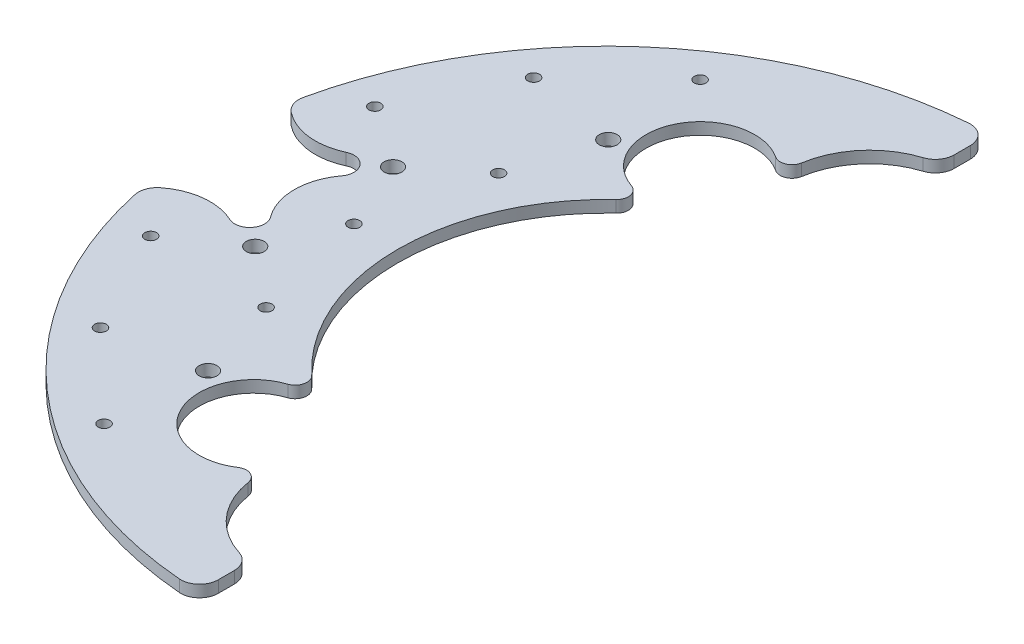
SolidWorks part; units mm, degrees
material "G-10 Garolite"
ref_plane "Front Plane" through (0, 0, 0) normal (0, 0, 1) x (1, 0, 0)
ref_plane "Top Plane" through (0, 0, 0) normal (0, 1, 0) x (1, 0, 0)
ref_plane "Right Plane" through (0, 0, 0) normal (1, 0, 0) x (0, 0, -1)
sketch "Sketch1" plane through (0, 0, 0) normal (0, 1, 0) x (1, 0, 0)
  line L0 (0, 0) -> (0, 53.6196) construction
  line L1 (0, 0) -> (0, -53.6196) construction
  line L2 (-1.5875, 53.5961) -> (-1.5875, 46.7173)
  line L3 (-1.5875, -46.7173) -> (-1.5875, -53.5961)
  arc A0 (-7.2005, 27.2547) -> (-7.2005, -27.2547) centre (0, 0) ccw
  arc A1 (-1.5875, 53.5961) -> (-52.743, 9.6559) centre (0, 0) ccw
  circle A4 centre (-28.468, 38.9692) radius 0.7937
  circle A6 centre (-39.2868, 28.0281) radius 0.7937
  circle A7 centre (-30.5898, 15.1396) radius 0.7937
  circle A8 centre (-46.1119, 14.2379) radius 0.7937
  circle A9 centre (-34.1313, 0) radius 0.7937
  circle A10 centre (-46.1119, -14.2379) radius 0.7937
  circle A11 centre (-30.5898, -15.1396) radius 0.7937
  circle A12 centre (-39.2868, -28.0281) radius 0.7937
  circle A13 centre (-28.468, -38.9692) radius 0.7937
  arc A14 (-7.2005, -27.2547) -> (-1.5875, -46.7173) centre (0, -35.7188) ccw
  circle A15 centre (-27.0529, 26.8282) radius 1.2065
  circle A16 centre (-38.0141, 8.8923) radius 1.2065
  circle A17 centre (-38.0141, -8.8923) radius 1.2065
  circle A18 centre (-27.0529, -26.8282) radius 1.2065
  arc A19 (-1.5875, 46.7173) -> (-7.2005, 27.2547) centre (0, 35.7188) ccw
  arc A26 (-52.743, -9.6559) -> (-1.5875, -53.5961) centre (0, 0) ccw
  arc A36 (-42.7001, -6.9355) -> (-52.743, -9.6559) centre (-46.1119, -14.2379) ccw
  arc A37 (-42.7001, -6.9355) -> (-40.743, -4.6098) centre (-42.0339, -5.5098) ccw
  arc A38 (-40.743, 4.6098) -> (-40.743, -4.6098) centre (-34.1313, 0) ccw
  arc A39 (-40.743, 4.6098) -> (-42.7001, 6.9355) centre (-42.0339, 5.5098) ccw
  arc A40 (-52.743, 9.6559) -> (-42.7001, 6.9355) centre (-46.1119, 14.2379) ccw
  dimension "D3" = 1.5875
  dimension "D6" = 2.413
  dimension "D4" = 3.175
sketch "Sketch4" plane through (0, 0, 0) normal (0, 1, 0) x (1, 0, 0)
  line L0 (0, 0) -> (0, 53.6196) construction
  line L1 (0, 0) -> (0, -53.6196) construction
  line L2 (-1.5875, 53.5961) -> (-1.5875, 46.7173)
  line L3 (-1.5875, -46.7173) -> (-1.5875, -53.5961)
  arc A0 (-7.2005, 27.2547) -> (-7.2005, -27.2547) centre (0, 0) ccw
  arc A1 (-1.5875, 53.5961) -> (-52.675, 10.0204) centre (0, 0) ccw
  circle A4 centre (-27.61, 40.3535) radius 0.7937
  circle A6 centre (-39.1254, 29.3244) radius 0.7937
  circle A7 centre (-30.2838, 15.7427) radius 0.7937
  circle A8 centre (-46.48, 15.1767) radius 0.7937
  circle A9 centre (-34.1313, 0) radius 0.7937
  circle A10 centre (-46.48, -15.1767) radius 0.7937
  circle A11 centre (-30.2838, -15.7427) radius 0.7937
  circle A12 centre (-39.1254, -29.3244) radius 0.7937
  circle A13 centre (-27.61, -40.3535) radius 0.7937
  arc A14 (-7.2005, -27.2547) -> (-1.5875, -46.7173) centre (0, -35.7188) ccw
  circle A15 centre (-26.7885, 27.0922) radius 1.2065
  circle A16 centre (-38.1676, 9.328) radius 1.2065
  circle A17 centre (-38.1676, -9.328) radius 1.2065
  circle A18 centre (-26.7885, -27.0922) radius 1.2065
  arc A19 (-1.5875, 46.7173) -> (-7.2005, 27.2547) centre (0, 35.7188) ccw
  circle A24 centre (-38.1676, -9.328) radius 3.175
  circle A25 centre (-38.1676, 9.328) radius 3.175
  arc A26 (-52.675, -10.0204) -> (-1.5875, -53.5961) centre (0, 0) ccw
  circle A27 centre (-17.4625, 30.2459) radius 7.1438
  circle A28 centre (-17.4625, -30.2459) radius 7.1438
  circle A29 centre (0, 0) radius 34.925 construction
  arc A36 (-41.1212, -9.156) -> (-52.675, -10.0204) centre (-46.48, -15.1767) ccw
  arc A38 (-38.9366, 6.4711) -> (-38.9366, -6.4711) centre (-34.1313, 0) ccw
  arc A40 (-52.675, 10.0204) -> (-41.1212, 9.156) centre (-46.48, 15.1767) ccw
  arc A51 (-9.2196, -25.8848) -> (-11.0854, -28.0492) centre (0, -35.7188) ccw
  arc A52 (-17.557, -36.9901) -> (-11.0854, -28.0492) centre (-17.4625, -30.2459) ccw
  arc A127 (-17.557, -36.9901) -> (-19.6182, -39.3062) centre (-17.5857, -39.0398) ccw
  arc A128 (-25.9575, -48.2425) -> (-19.6182, -39.3062) centre (-27.61, -40.3535) ccw
  arc A137 (-11.0854, 28.0492) -> (-9.2196, 25.8848) centre (0, 35.7188) ccw
  arc A138 (-11.0854, 28.0492) -> (-17.557, 36.9901) centre (-17.4625, 30.2459) ccw
  arc A139 (-19.6182, 39.3062) -> (-17.557, 36.9901) centre (-17.5857, 39.0398) ccw
  arc A140 (-19.6182, 39.3062) -> (-25.9575, 48.2425) centre (-27.61, 40.3535) ccw
  dimension "D3" = 1.5875
  dimension "D6" = 2.413
  dimension "D7" = 14.2875
  dimension "D8" = 17.4625
  dimension "D9" = 60.4919
  dimension "D10" = 69.85
  dimension "D13" = 6.35
  dimension "D4" = 3.175
sketch "Sketch3" plane through (0, 0, 0) normal (0, 1, 0) x (1, 0, 0)
  line L0 (0, 0) -> (0, 53.6196) construction
  line L1 (0, 0) -> (0, -53.6196) construction
  line L2 (-1.5875, 53.5961) -> (-1.5875, 46.7173)
  line L3 (-1.5875, -46.7173) -> (-1.5875, -53.5961)
  arc A0 (-7.2005, 27.2547) -> (-7.2005, -27.2547) centre (0, 0) ccw
  arc A1 (-1.5875, 53.5961) -> (-52.743, 9.6559) centre (0, 0) ccw
  circle A4 centre (-28.468, 38.9692) radius 0.7937
  circle A6 centre (-39.2868, 28.0281) radius 0.7937
  circle A7 centre (-30.5898, 15.1396) radius 0.7937
  circle A8 centre (-46.1119, 14.2379) radius 0.7937
  circle A9 centre (-34.1313, 0) radius 0.7937
  circle A10 centre (-46.1119, -14.2379) radius 0.7937
  circle A11 centre (-30.5898, -15.1396) radius 0.7937
  circle A12 centre (-39.2868, -28.0281) radius 0.7937
  circle A13 centre (-28.468, -38.9692) radius 0.7937
  arc A14 (-7.2005, -27.2547) -> (-1.5875, -46.7173) centre (0, -35.7188) ccw
  circle A15 centre (-27.0529, 26.8282) radius 1.2065
  circle A16 centre (-38.0141, 8.8923) radius 1.2065
  circle A17 centre (-38.0141, -8.8923) radius 1.2065
  circle A18 centre (-27.0529, -26.8282) radius 1.2065
  arc A19 (-1.5875, 46.7173) -> (-7.2005, 27.2547) centre (0, 35.7188) ccw
  arc A26 (-52.743, -9.6559) -> (-1.5875, -53.5961) centre (0, 0) ccw
  circle A27 centre (-17.4625, 30.2459) radius 5.08
  circle A28 centre (-17.4625, -30.2459) radius 5.08
  circle A29 centre (0, 0) radius 34.925 construction
  arc A36 (-42.7001, -6.9355) -> (-52.743, -9.6559) centre (-46.1119, -14.2379) ccw
  arc A37 (-42.7001, -6.9355) -> (-40.743, -4.6098) centre (-42.0339, -5.5098) ccw
  arc A38 (-40.743, 4.6098) -> (-40.743, -4.6098) centre (-34.1313, 0) ccw
  arc A39 (-40.743, 4.6098) -> (-42.7001, 6.9355) centre (-42.0339, 5.5098) ccw
  arc A40 (-52.743, 9.6559) -> (-42.7001, 6.9355) centre (-46.1119, 14.2379) ccw
  arc A44 (-18.8986, 37.7435) -> (-28.0384, 48.6073) centre (-28.468, 38.9692) ccw
  arc A45 (-9.9625, 28.8224) -> (-18.8986, 37.7435) centre (-17.4625, 30.2459) ccw
  arc A51 (-18.8986, -37.7435) -> (-9.9625, -28.8224) centre (-17.4625, -30.2459) ccw
  arc A52 (-28.0384, -48.6073) -> (-18.8986, -37.7435) centre (-28.468, -38.9692) ccw
  dimension "D3" = 1.5875
  dimension "D6" = 2.413
  dimension "D7" = 10.16
  dimension "D8" = 17.4625
  dimension "D9" = 60.4919
  dimension "D10" = 69.85
  dimension "D4" = 3.175
sketch "Sketch2" plane through (0, 0, 0) normal (0, 1, 0) x (1, 0, 0)
  line L0 (-17.4625, 30.2459) -> (0, 0) construction
  line L1 (0, 0) -> (-17.4625, -30.2459) construction
  line L2 (-1.5875, 46.7173) -> (-1.5875, 53.5961)
  line L3 (-1.5875, -53.5961) -> (-1.5875, -46.7173)
  line L4 (-1.5875, 48.7324) -> (-1.5875, 50.9126)
  line L5 (-1.5875, -50.9126) -> (-1.5875, -48.7324)
  line L6 (0, 0) -> (0, 53.6196) construction
  arc A0 (-51.4928, -8.865) -> (-52.3951, -11.3937) centre (-49.9131, -10.854) ccw
  circle A1 centre (-39.1254, 29.3244) radius 0.7937 construction
  circle A2 centre (-39.1254, 29.3244) radius 0.7937
  circle A4 centre (-27.61, 40.3535) radius 0.7937 construction
  circle A5 centre (-30.2838, -15.7427) radius 0.7937 construction
  circle A6 centre (-30.2838, -15.7427) radius 0.7937
  circle A7 centre (-46.48, -15.1767) radius 0.7938 construction
  circle A8 centre (-46.48, -15.1767) radius 0.7937
  circle A9 centre (-34.1313, 0) radius 0.7938
  circle A10 centre (-34.1313, 0) radius 0.7937
  circle A11 centre (-46.48, 15.1767) radius 0.7938 construction
  circle A12 centre (-46.48, 15.1767) radius 0.7937
  circle A13 centre (-30.2838, 15.7427) radius 0.7937 construction
  circle A14 centre (-30.2838, 15.7427) radius 0.7937
  circle A15 centre (-38.1676, -9.328) radius 1.2065 construction
  circle A16 centre (-38.1676, -9.328) radius 1.2065
  circle A17 centre (-38.1676, 9.328) radius 1.2065 construction
  circle A18 centre (-38.1676, 9.328) radius 1.2065
  circle A19 centre (-26.7885, 27.0922) radius 1.2065 construction
  circle A20 centre (-26.7885, 27.0922) radius 1.2065
  circle A21 centre (-27.61, 40.3535) radius 0.7937
  circle A23 centre (-39.1254, -29.3244) radius 0.7938 construction
  circle A24 centre (-39.1254, -29.3244) radius 0.7937
  circle A25 centre (-26.7885, -27.0922) radius 1.2065 construction
  circle A26 centre (-26.7885, -27.0922) radius 1.2065
  arc A27 (-51.4928, 8.865) -> (-52.3951, 11.3937) centre (-49.9131, 10.854) cw
  arc A28 (-4.3327, -53.4442) -> (-1.5875, -50.9126) centre (-4.1275, -50.9126) ccw
  arc A29 (-1.5875, -48.7324) -> (-3.3596, -46.3112) centre (-4.1275, -48.7324) ccw
  arc A30 (-13.4132, -36.3991) -> (-10.9729, -37.4744) centre (-12.5405, -37.7252) cw
  arc A31 (-13.4132, 36.3991) -> (-10.9729, 37.4744) centre (-12.5405, 37.7252) ccw
  arc A32 (-3.3596, 46.3112) -> (-1.5875, 48.7324) centre (-4.1275, 48.7324) ccw
  arc A33 (-1.5875, 50.9126) -> (-4.3327, 53.4442) centre (-4.1275, 50.9126) ccw
  arc A34 (-13.4132, 36.3991) -> (-19.8172, 23.2665) centre (-17.4625, 30.2459) ccw
  arc A35 (-19.8172, -23.2665) -> (-13.4132, -36.3991) centre (-17.4625, -30.2459) ccw
  arc A36 (-42.7001, -6.9355) -> (-40.743, -4.6098) centre (-42.0339, -5.5098) ccw
  arc A37 (-40.743, 4.6098) -> (-40.743, -4.6098) centre (-34.1313, 0) ccw
  arc A38 (-40.743, 4.6098) -> (-42.7001, 6.9355) centre (-42.0339, 5.5098) ccw
  arc A39 (-52.743, 9.6559) -> (-42.7001, 6.9355) centre (-46.1119, 14.2379) ccw
  arc A40 (-1.5875, 53.5961) -> (-52.743, 9.6559) centre (0, 0) ccw
  arc A41 (-1.5875, 46.7173) -> (-7.2005, 27.2547) centre (0, 35.7188) ccw
  arc A42 (-7.2005, 27.2547) -> (-7.2005, -27.2547) centre (0, 0) ccw
  arc A43 (-7.2005, -27.2547) -> (-1.5875, -46.7173) centre (0, -35.7188) ccw
  arc A44 (-52.743, -9.6559) -> (-1.5875, -53.5961) centre (0, 0) ccw
  arc A45 (-42.7001, -6.9355) -> (-52.743, -9.6559) centre (-46.1119, -14.2379) ccw
  arc A46 (-41.1212, -9.156) -> (-52.675, -10.0204) centre (-46.48, -15.1767) ccw construction
  arc A47 (-38.9366, 6.4711) -> (-38.9366, -6.4711) centre (-34.1313, 0) ccw construction
  arc A48 (-52.675, 10.0204) -> (-41.1212, 9.156) centre (-46.48, 15.1767) ccw construction
  arc A49 (-43.0582, -7.879) -> (-51.4928, -8.865) centre (-46.48, -15.1767) ccw
  arc A50 (-4.3327, 53.4442) -> (-52.3951, 11.3937) centre (0, 0) ccw
  arc A51 (-3.3596, 46.3112) -> (-10.9729, 37.4744) centre (0, 35.7188) ccw
  arc A52 (-19.8172, 23.2665) -> (-19.2412, 20.6021) centre (-20.3247, 21.7623) cw
  arc A53 (-7.2005, -27.2547) -> (-1.5875, -46.7173) centre (0, -35.7188) ccw construction
  arc A54 (-52.3951, -11.3937) -> (-4.3327, -53.4442) centre (0, 0) ccw
  arc A55 (-51.4928, 8.865) -> (-43.0582, 7.879) centre (-46.48, 15.1767) ccw
  circle A56 centre (0, 0) radius 34.925 construction
  circle A57 centre (-17.4625, 30.2459) radius 6.096 construction
  circle A58 centre (-17.4625, -30.2459) radius 6.096 construction
  circle A59 centre (-26.7885, -27.0922) radius 2.54 construction
  circle A60 centre (-38.1676, -9.328) radius 2.54 construction
  circle A61 centre (-38.1676, 9.328) radius 2.54 construction
  circle A62 centre (-26.7885, 27.0922) radius 2.54 construction
  arc A63 (-18.8986, -37.7435) -> (-9.9625, -28.8224) centre (-17.4625, -30.2459) ccw construction
  arc A64 (-28.0384, -48.6073) -> (-18.8986, -37.7435) centre (-28.468, -38.9692) ccw construction
  arc A65 (-18.8986, -37.7435) -> (-11.0284, -34.3542) centre (-17.4625, -30.2459) ccw construction
  arc A66 (-24.4297, -47.731) -> (-18.8986, -37.7435) centre (-28.468, -38.9692) ccw construction
  arc A67 (-18.8986, 37.7435) -> (-28.0384, 48.6073) centre (-28.468, 38.9692) ccw construction
  arc A68 (-19.2412, 20.6021) -> (-19.2412, -20.6021) centre (0, 0) ccw
  arc A69 (-18.8986, 37.7435) -> (-24.4297, 47.731) centre (-28.468, 38.9692) ccw construction
  arc A70 (-7.2005, 27.2547) -> (-7.2005, -27.2547) centre (0, 0) ccw construction
  arc A71 (-11.0284, 34.3542) -> (-18.8986, 37.7435) centre (-17.4625, 30.2459) ccw construction
  arc A72 (-40.5808, 4.8342) -> (-40.5808, -4.8342) centre (-34.1313, 0) ccw
  arc A73 (-19.8172, -23.2665) -> (-19.2412, -20.6021) centre (-20.3247, -21.7623) ccw
  arc A74 (-10.9729, -37.4744) -> (-3.3596, -46.3112) centre (0, -35.7188) ccw
  arc A75 (-43.0582, 7.879) -> (-40.5808, 4.8342) centre (-42.1994, 6.0474) cw
  arc A76 (-40.5808, -4.8342) -> (-43.0582, -7.879) centre (-42.1994, -6.0474) cw
  circle A77 centre (-38.1676, 9.328) radius 3.175 construction
  circle A79 centre (-27.61, -40.3535) radius 0.7937 construction
  circle A80 centre (-27.61, -40.3535) radius 0.7937
  dimension "D15" = 2.54
  dimension "D16" = 14.732
  dimension "D17" = 12.192
  dimension "D18" = 5.08
  dimension "D19" = 69.85
  dimension "D21" = 1.5875
  dimension "D20" = 30
  dimension "D5" = 0
  dimension "D14" = 0
extrude "Boss-Extrude1" add sketch "Sketch2" along normal blind 1.6
